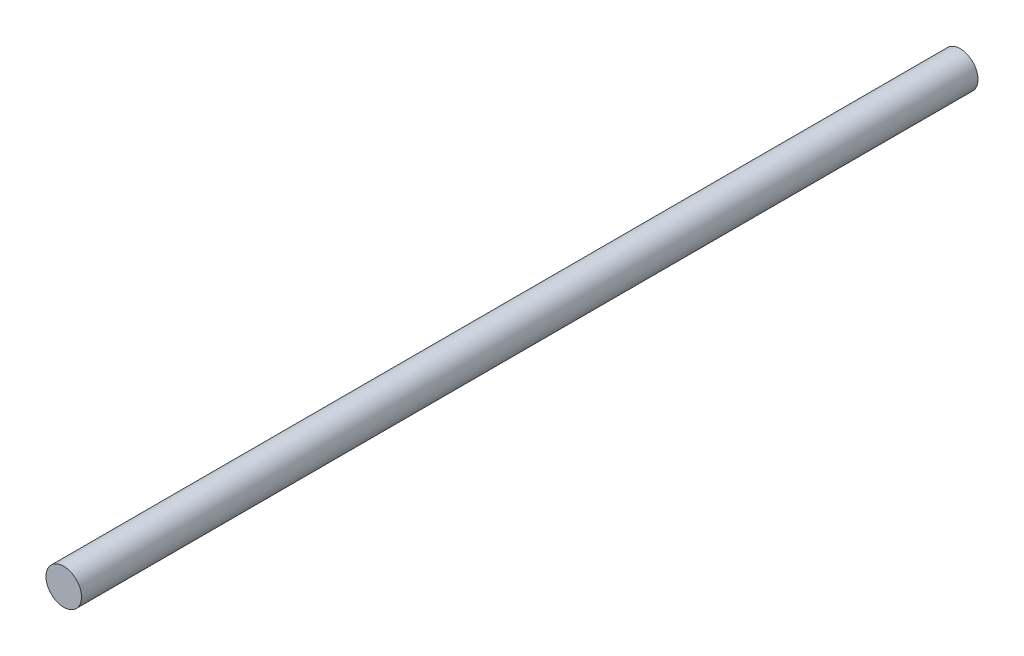
SolidWorks part; units mm, degrees
ref_plane "前视基准面" through (0, 0, 0) normal (0, 0, 1) x (1, 0, 0)
ref_plane "上视基准面" through (0, 0, 0) normal (0, 1, 0) x (1, 0, 0)
ref_plane "右视基准面" through (0, 0, 0) normal (1, 0, 0) x (0, 0, -1)
other "Configuration Table"
sketch "草图1" plane through (0, 0, 0) normal (0, 0, 1) x (1, 0, 0)
  circle A0 centre (0, 0) radius 3
  dimension "diameter" = 6
extrude "Cable_envelope" add sketch "草图1" along normal blind 151.3
